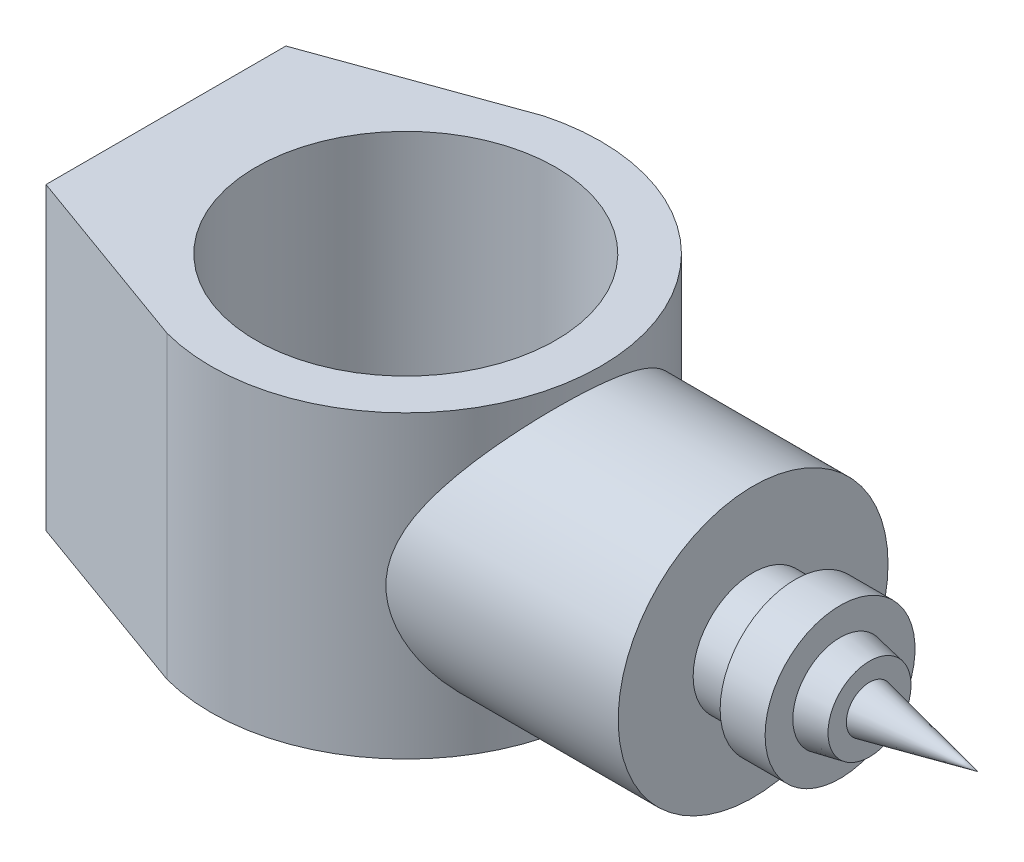
SolidWorks part; units mm, degrees
ref_plane "Front Plane" through (0, 0, 0) normal (0, 0, 1) x (1, 0, 0)
ref_plane "Top Plane" through (0, 0, 0) normal (0, 1, 0) x (1, 0, 0)
ref_plane "Right Plane" through (0, 0, 0) normal (1, 0, 0) x (0, 0, -1)
sketch "Sketch1" plane through (0, 0, 0) normal (0, 1, 0) x (1, 0, 0)
  line L0 (-2032, 1121.9816) -> (-428.0436, 1700.5284)
  line L1 (-2032, -910.0184) -> (-2032, 1121.9816)
  line L2 (-2032, -910.0184) -> (-428.0436, -1488.5653)
  arc A0 (-428.0436, -1488.5653) -> (-428.0436, 1700.5284) centre (0, 105.9816) ccw
  circle A1 centre (0, 105.9816) radius 1270
  point P7 (-2032, 105.9816)
  dimension "D1" = 3302
  dimension "D2" = 2540
  dimension "D3" = 2032
  dimension "D4" = 2032
extrude "Boss-Extrude1" add sketch "Sketch1" along normal mid plane 2540
ref_plane "Plane5" through (3048, 0, 0) normal (1, 0, 0) x (0, 0, -1)
sketch "Sketch4" plane through (3048, 0, 0) normal (1, 0, 0) x (0, 0, -1)
  circle A0 centre (0, 0) radius 1143
  dimension "D1" = 2286
extrude "Boss-Extrude4" add sketch "Sketch4" against normal up to next
sketch "Sketch8" plane through (0, 0, 0) normal (0, 1, 0) x (1, 0, 0)
  line L0 (0, 0) -> (6850.0854, 0) construction
  line L1 (-1397, 0) -> (1397, 0) construction
  line L2 (3048, 0) -> (3048, -508)
  line L3 (3048, -1143) -> (3048, 1143) construction
  line L4 (3048, -508) -> (3403.6, -508)
  line L5 (3403.6, -508) -> (3403.6, -635)
  line L6 (3403.6, -635) -> (3784.6, -635)
  line L7 (3784.6, -635) -> (3784.6, -400.0369)
  line L8 (3784.6, -400.0369) -> (4033.9521, -351.6683)
  line L9 (4033.9521, -351.6683) -> (4033.9521, -196.4054)
  line L10 (4033.9521, -196.4054) -> (4953, 0)
  line L11 (4953, 0) -> (3048, 0)
  dimension "D1" = 508
  dimension "D2" = 355.6
  dimension "D3" = 127
  dimension "D4" = 381
  dimension "D5" = 254
  dimension "D6" = 939.8
  dimension "D7" = 1905
revolve "Revolve3" add sketch "Sketch8" angle 360 about L0
